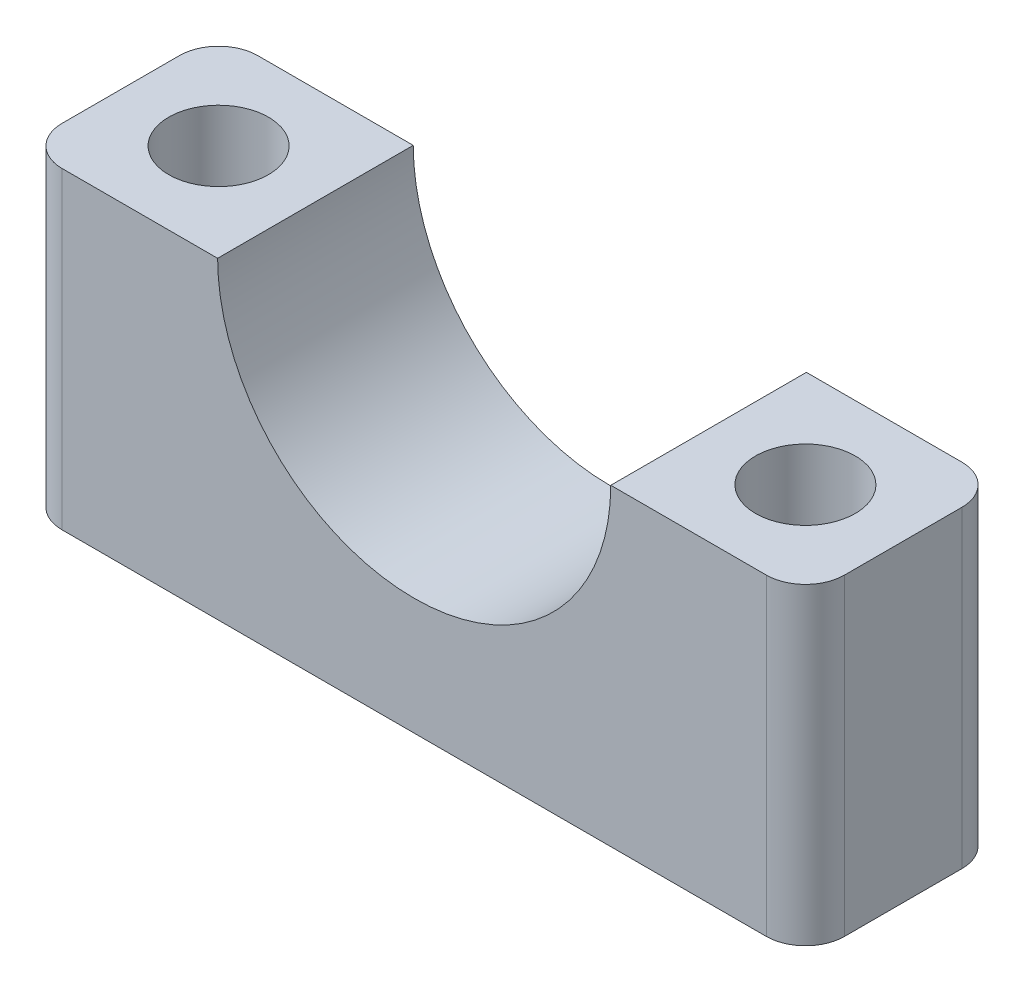
SolidWorks part; units mm, degrees
ref_plane "Front Plane" through (0, 0, 0) normal (0, 0, 1) x (1, 0, 0)
ref_plane "Top Plane" through (0, 0, 0) normal (0, 1, 0) x (1, 0, 0)
ref_plane "Right Plane" through (0, 0, 0) normal (1, 0, 0) x (0, 0, -1)
sketch "Sketch1" plane through (0, 0, 0) normal (0, 0, 1) x (1, 0, 0)
  line L0 (-20, 8) -> (20, -8) construction
  line L1 (-20, 8) -> (20, 8)
  line L2 (-20, 8) -> (-20, -8)
  line L3 (-20, -8) -> (20, -8)
  line L4 (20, 8) -> (20, -8)
  point P4 (0, 0)
  dimension "D1" = 40
  dimension "D2" = 16
extrude "Boss-Extrude1" add sketch "Sketch1" along normal blind 10
fillet "Fillet1" radius 2 4 edges at (20, 0, 0) (20, 0, 10) (-20, 0, 10) (-20, 0, 0)
sketch "Sketch3" plane through (0, 0, 10) normal (0, 0, 1) x (1, 0, 0)
  line L0 (0, 8) -> (0, 8.02) construction
  line L1 (18, 8) -> (-18, 8) construction
  circle A0 centre (0, 8.02) radius 10.05
  dimension "D2" = 20.1
  dimension "D1" = 0.02
extrude "Cut-Extrude1" cut sketch "Sketch3" against normal through all
sketch "Sketch4" plane through (0, 8, 0) normal (0, 1, 0) x (1, 0, 0)
  line L0 (-20, -5) -> (-15, -5) construction
  line L1 (-20, -8) -> (-20, -2) construction
  line L2 (20, -5) -> (15, -5) construction
  line L3 (20, -8) -> (20, -2) construction
  circle A0 centre (-15, -5) radius 2.55
  circle A1 centre (15, -5) radius 2.55
  dimension "D3" = 5.1
  dimension "D4" = 5.1
  dimension "D1" = 5
  dimension "D2" = 5
extrude "Cut-Extrude2" cut sketch "Sketch4" against normal through all
